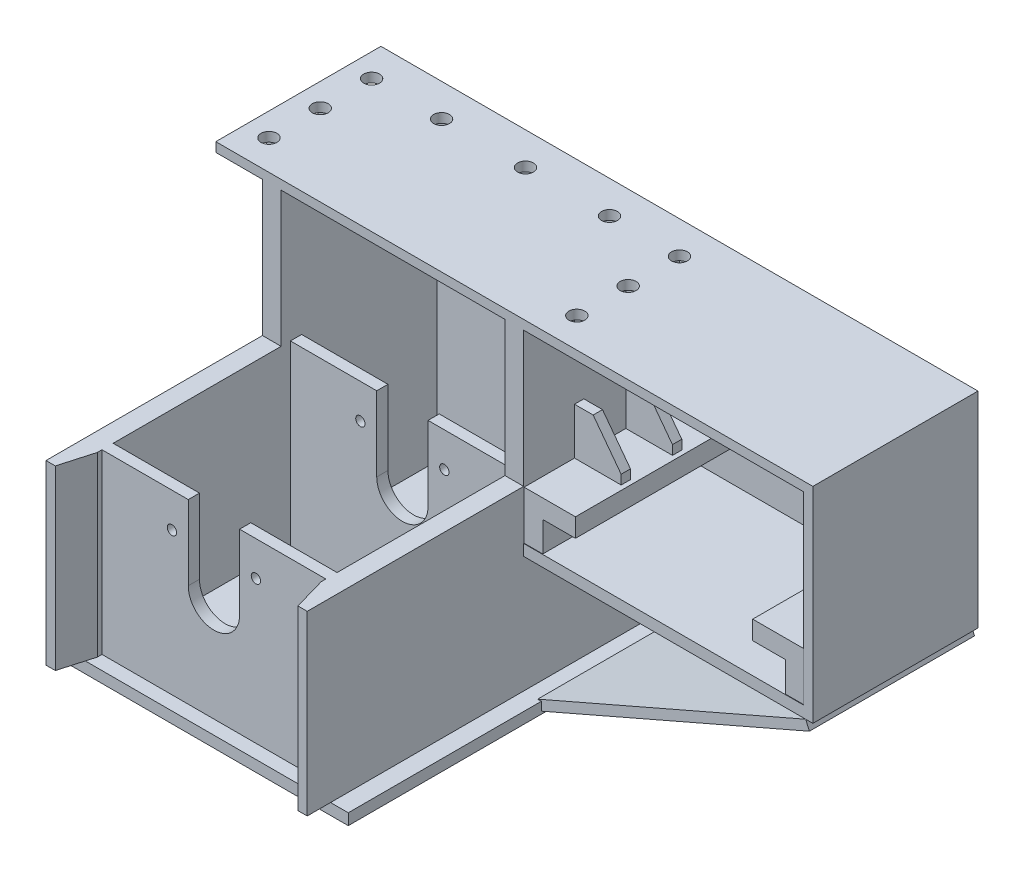
SolidWorks part; units mm, degrees
ref_plane "前视基准面" through (0, 0, 0) normal (0, 0, 1) x (1, 0, 0)
ref_plane "上视基准面" through (0, 0, 0) normal (0, 1, 0) x (1, 0, 0)
ref_plane "右视基准面" through (0, 0, 0) normal (1, 0, 0) x (0, 0, -1)
sketch "草图1" plane through (0, 0, 0) normal (0, 1, 0) x (1, 0, 0)
  line L0 (450, -858) -> (450, 49142) construction
  line L1 (0, 0) -> (640, 0)
  line L2 (0, 0) -> (0, 177)
  line L3 (0, 177) -> (640, 177)
  line L4 (640, 0) -> (640, 177)
  circle A0 centre (615, 142) radius 8.5
  circle A1 centre (615, 87) radius 8.5
  circle A2 centre (615, 32) radius 8.5
  circle A3 centre (540, 142) radius 8.5
  circle A4 centre (450, 142) radius 8.5
  circle A5 centre (360, 142) radius 8.5
  circle A6 centre (285, 142) radius 8.5
  circle A7 centre (285, 32) radius 8.5
  circle A8 centre (285, 87) radius 8.5
  dimension "D3" = 17
  dimension "D1" = 640
  dimension "D2" = 177
  dimension "D4" = 25
  dimension "D5" = 55
  dimension "D6" = 32
  dimension "D7" = 55
  dimension "D8" = 165
  dimension "D9" = 90
  dimension "D10" = 165
  dimension "D11" = 90
extrude "凸台-拉伸1" add sketch "草图1" along normal blind 10
sketch "草图2" plane through (0, 0, 0) normal (0, -1, 0) x (1, 0, 0)
  line L0 (450, -1145) -> (450, 48855) construction
  line L2 (640, -177) -> (0, -177) construction
  line L3 (590, -177) -> (570, -177)
  line L4 (590, -177) -> (590, 0)
  line L5 (590, 0) -> (570, 0)
  line L6 (570, -177) -> (570, 0)
  line L7 (0, 0) -> (640, 0) construction
  line L9 (330, -177) -> (310, -177)
  line L10 (330, -177) -> (330, 0)
  line L11 (330, 0) -> (310, 0)
  line L12 (310, -177) -> (310, 0)
  dimension "D1" = 20
  dimension "D2" = 20
  dimension "D3" = 120
  dimension "D4" = 120
extrude "凸台-拉伸2" add sketch "草图2" along normal blind 335
sketch "草图3" plane through (0, 0, 0) normal (0, 0, 1) x (1, 0, 0)
  line L0 (570, -335) -> (570, 0) construction
  line L1 (590, -335) -> (570, -335)
  line L2 (590, -335) -> (590, -145)
  line L3 (590, -145) -> (570, -145)
  line L4 (570, -335) -> (570, -145)
  line L5 (310, -335) -> (310, 0) construction
  line L6 (330, -335) -> (310, -335)
  line L7 (330, -335) -> (330, -145)
  line L8 (330, -145) -> (310, -145)
  line L9 (310, -335) -> (310, -145)
  dimension "D1" = 190
  dimension "D2" = 190
extrude "凸台-拉伸3" add sketch "草图3" along normal blind 232
sketch "草图4" plane through (0, -335, 0) normal (0, -1, 0) x (1, 0, 0)
  line L0 (330, 232) -> (320, 232)
  line L1 (310, 232) -> (330, 232) construction
  line L2 (320, 232) -> (330, 197)
  line L3 (330, -177) -> (330, 232) construction
  line L4 (330, 197) -> (330, 232)
  line L5 (570, 232) -> (580, 232)
  line L6 (570, 232) -> (590, 232) construction
  line L7 (580, 232) -> (570, 197)
  line L8 (570, 232) -> (570, -177) construction
  line L9 (570, 197) -> (570, 232)
  dimension "D1" = 35
  dimension "D2" = 10
  dimension "D3" = 10
  dimension "D4" = 35
extrude "切除-拉伸1" cut sketch "草图4" against normal through all
sketch "草图5" plane through (0, 0, 0) normal (0, -1, 0) x (-1, 0, 0)
  line L0 (-570, -197) -> (-570, 177) construction
  line L1 (-330, 177) -> (-570, 177)
  line L2 (-330, 177) -> (-330, 167)
  line L3 (-330, 167) -> (-570, 167)
  line L4 (-570, 177) -> (-570, 167)
  dimension "D1" = 10
extrude "凸台-拉伸4" add sketch "草图5" along normal blind 335
sketch "草图6" plane through (0, 0, -177) normal (0, 0, -1) x (-1, 0, 0)
  line L0 (-450, -1335) -> (-450, 48665) construction
  line L1 (-310, -335) -> (-590, -335) construction
  circle A0 centre (-450, -225) radius 35
  point P5 (-450, -335)
  dimension "D1" = 70
  dimension "D2" = 110
extrude "切除-拉伸2" cut sketch "草图6" against normal blind 10
sketch "草图7" plane through (310, 0, 0) normal (-1, 0, 0) x (0, 0, 1)
  line L0 (232, -335) -> (-177, -335) construction
  line L1 (-177, 0) -> (-167, 0)
  line L2 (-177, 0) -> (-177, -335)
  line L3 (-177, -335) -> (-167, -335)
  line L4 (-167, 0) -> (-167, -335)
  dimension "D1" = 10
extrude "凸台-拉伸5" add sketch "草图7" along normal blind 300
sketch "草图8" plane through (0, 0, -177) normal (0, 0, -1) x (-1, 0, 0)
  line L0 (-10, -211) -> (-295, -335)
  line L1 (-10, 0) -> (-10, -335) construction
  line L2 (-10, -335) -> (-590, -335) construction
  line L3 (-295, -335) -> (-10, -335)
  line L4 (-10, -335) -> (-10, -211)
  line L5 (-640, 10) -> (0, 10) construction
  circle A0 centre (-217, -76) radius 6
  circle A1 centre (-103, -76) radius 6
  circle A2 centre (-217, -119) radius 6
  circle A3 centre (-103, -119) radius 6
  dimension "D3" = 12
  dimension "D1" = 124
  dimension "D2" = 285
  dimension "D4" = 93
  dimension "D5" = 114
  dimension "D6" = 43
  dimension "D7" = 129
extrude "切除-拉伸3" cut sketch "草图8" against normal blind 10
sketch "草图9" plane through (10, 0, 0) normal (-1, 0, 0) x (0, 0, 1)
  line L1 (-177, 0) -> (0, 0)
  line L2 (-177, 0) -> (-177, -210)
  line L3 (-177, -210) -> (0, -210)
  line L4 (0, 0) -> (0, -210)
  dimension "D1" = 177
  dimension "D2" = 210
extrude "凸台-拉伸6" add sketch "草图9" along normal blind 10
sketch "草图11" plane through (0, 0, -177) normal (0, 0, -1) x (-1, 0, 0)
  line L0 (-7.7108, -210.004) -> (-295, -335)
  line L1 (-295, -335) -> (-291.0104, -344.1697)
  line L2 (-291.0104, -344.1697) -> (-3.712, -219.1697)
  line L3 (-3.712, -219.1697) -> (-7.6976, -210.0092)
  line L4 (-10, -211) -> (-295, -335) construction
  line L5 (0, -210) -> (-10, -210) construction
  line L6 (-7.6976, -210.0092) -> (-7.7108, -210.004)
  point P0 (-7.7016, -210)
  dimension "D2" = 10
extrude "凸台-拉伸7" add sketch "草图11" against normal blind 177 separate body
ref_plane "基准面1" through (0, 0, 180) normal (0, 0, 1) x (1, 0, 0)
sketch "草图12" plane through (0, 0, 180) normal (0, 0, 1) x (1, 0, 0)
  line L0 (330, -335) -> (570, -335)
  line L1 (570, -335) -> (570, -145)
  line L2 (330, -145) -> (422.5, -145)
  line L3 (330, -145) -> (330, -335)
  line L4 (450, -1335) -> (450, 48665) construction
  line L5 (-550, -225) -> (49450, -225) construction
  line L6 (422.5, -145) -> (422.5, -225)
  line L7 (570, -145) -> (477.5, -145)
  line L8 (477.5, -145) -> (477.5, -225)
  line L9 (-638.5489, -182) -> (49361.4511, -182) construction
  arc A0 (422.5, -225) -> (477.5, -225) centre (450, -225) ccw
  circle A1 centre (405, -182) radius 5
  circle A2 centre (495, -182) radius 5
  point P11 (450, -335)
  dimension "D1" = 27.5
  dimension "D3" = 10
  dimension "D2" = 43
  dimension "D4" = 45
  dimension "D5" = 45
extrude "凸台-拉伸8" add sketch "草图12" along normal blind 12
pattern_linear "阵列(线性)2" count 2 spacing 202 along (0, 0, -1) of "凸台-拉伸8"
sketch "草图14" plane through (0, 0, -167) normal (0, 0, 1) x (1, 0, 0)
  line L0 (310, -335) -> (310, 0) construction
  line L1 (10, -210) -> (310, -210)
  line L2 (10, -210) -> (10, -198)
  line L3 (10, -198) -> (310, -198)
  line L4 (310, -210) -> (310, -198)
  dimension "D1" = 12
extrude "凸台-拉伸9" add sketch "草图14" along normal blind 167
sketch "草图15" plane through (10, 0, 0) normal (1, 0, 0) x (0, 0, -1)
  line L0 (0, -198) -> (167, -198) construction
  line L1 (0.5, -166) -> (166.5, -166)
  line L2 (0.5, -166) -> (0.5, -198)
  line L3 (0.5, -198) -> (166.5, -198)
  line L4 (166.5, -166) -> (166.5, -198)
  line L5 (167, -198) -> (167, 0) construction
  line L6 (0, -198) -> (0, 0) construction
  dimension "D1" = 32
  dimension "D2" = 0.5
  dimension "D3" = 0.5
extrude "凸台-拉伸10" add sketch "草图15" along normal blind 20
sketch "草图16" plane through (0, 0, -0.5) normal (0, 0, 1) x (1, 0, 0)
  line L0 (310, -146) -> (310, -198)
  line L1 (10, -166) -> (65, -166)
  line L2 (10, -166) -> (10, -146)
  line L3 (10, -146) -> (65, -146)
  line L4 (65, -166) -> (65, -146)
  line L6 (310, -198) -> (290, -198)
  line L7 (310, -198) -> (10, -198) construction
  line L8 (290, -198) -> (290, -166)
  line L9 (290, -166) -> (255, -166)
  line L10 (255, -166) -> (255, -146)
  line L11 (255, -146) -> (310, -146)
  dimension "D1" = 55
  dimension "D2" = 20
  dimension "D3" = 20
extrude "凸台-拉伸11" add sketch "草图16" against normal blind 166
sketch "草图17" plane through (0, 0, -0.5) normal (0, 0, 1) x (1, 0, 0)
  line L0 (10, -146) -> (60, -146)
  line L2 (65, -146) -> (10, -146) construction
  line L3 (60, -146) -> (60, -136)
  line L6 (60, -136) -> (30, -96)
  line L7 (30, -96) -> (10, -96)
  line L9 (10, -96) -> (10, -146)
  line L10 (310, -146) -> (260, -146)
  line L11 (260, -146) -> (260, -136)
  line L12 (260, -136) -> (290, -96)
  line L13 (290, -96) -> (310, -96)
  line L15 (310, -96) -> (310, -146)
  dimension "D1" = 50
  dimension "D2" = 50
  dimension "D3" = 50
  dimension "D4" = 50
  dimension "D5" = 20
  dimension "D6" = 10
  dimension "D7" = 10
  dimension "D8" = 20
extrude "凸台-拉伸12" add sketch "草图17" against normal blind 166
sketch "草图18" plane through (0, -96, 0) normal (0, 1, 0) x (1, 0, 0)
  line L0 (285, 142) -> (285, 87) construction
  line L1 (285, 87) -> (285, 32) construction
  line L2 (-715, 114.5) -> (49285, 114.5) construction
  line L3 (-715, 59.5) -> (49285, 59.5) construction
  line L4 (-715, 87) -> (49285, 87) construction
  line L6 (10, 166.5) -> (310, 166.5)
  line L7 (10, 166.5) -> (10, 119.5)
  line L8 (10, 119.5) -> (310, 119.5)
  line L9 (310, 166.5) -> (310, 119.5)
  line L10 (10, 109.5) -> (310, 109.5)
  line L11 (10, 109.5) -> (10, 64.5)
  line L12 (10, 64.5) -> (310, 64.5)
  line L13 (310, 109.5) -> (310, 64.5)
  line L14 (10, 54.5) -> (310, 54.5)
  line L15 (10, 54.5) -> (10, 0.5)
  line L16 (10, 0.5) -> (310, 0.5)
  line L17 (310, 54.5) -> (310, 0.5)
  line L18 (10, 166.5) -> (10, 0.5) construction
  line L19 (310, 166.5) -> (310, 0.5) construction
  line L20 (310, 0.5) -> (290, 0.5) construction
  line L21 (310, 166.5) -> (290, 166.5) construction
  point P8 (285, 114.5)
  point P15 (285, 59.5)
  dimension "D1" = 10
  dimension "D2" = 10
extrude "切除-拉伸4" cut sketch "草图18" against normal blind 50
ref_plane "基准面2" through (590, 0, 0) normal (1, 0, 0) x (0, 0, -1)
sketch "草图20" plane through (0, 0, -54.5) normal (0, 0, 1) x (1, 0, 0)
  line L0 (590, 0) -> (640, 0)
  line L1 (640, 0) -> (640, -30)
  line L2 (640, -30) -> (610, -50)
  line L3 (610, -50) -> (590, -50)
  line L4 (590, -145) -> (590, 0) construction
  line L5 (590, -50) -> (590, 0)
  line L6 (310, 0) -> (276.6667, 0)
  line L7 (10, 0) -> (310, 0) construction
  line L8 (276.6667, 0) -> (276.6667, -30)
  line L9 (276.6667, -30) -> (290, -50)
  line L10 (290, -50) -> (310, -50)
  line L11 (310, -198) -> (310, 0) construction
  line L12 (310, -50) -> (310, 0)
  line L13 (10, 0) -> (10, -50)
  line L14 (10, -198) -> (10, 0) construction
  line L15 (10, -50) -> (30, -50)
  line L16 (30, -50) -> (60, -30)
  line L17 (60, -30) -> (60, 0)
  line L18 (60, 0) -> (10, 0)
  dimension "D1" = 20
  dimension "D2" = 30
  dimension "D3" = 30
  dimension "D4" = 30
  dimension "D5" = 50
  dimension "D6" = 50
extrude "凸台-拉伸13" add sketch "草图20" against normal blind 10
pattern_linear "阵列(线性)1" count 2 spacing 55 along (0, 0, -1) of "凸台-拉伸13"
sketch "草图21" plane through (0, -335, 0) normal (0, -1, 0) x (-1, 0, 0)
  line L1 (-291.0104, 177) -> (-605, 177)
  line L2 (-291.0104, 177) -> (-291.0104, -207)
  line L3 (-291.0104, -207) -> (-605, -207)
  line L4 (-605, 177) -> (-605, -207)
  line L6 (-291.0104, 0) -> (-291.0104, 177) construction
  line L7 (-295, 177) -> (-590, 177) construction
  line L8 (-295, 0) -> (-295, 177) construction
  dimension "D1" = 310
  dimension "D2" = 384
extrude "凸台-拉伸18" add sketch "草图21" along normal blind 12
mirror "镜向1" about plane through (0, 0, 0) normal (1, 0, 0) of bodies 129
sketch "草图22" plane through (0, 10, 0) normal (0, 1, 0) x (1, 0, 0)
  line L0 (640, 0) -> (640, 177) construction
  line L1 (0, 177) -> (640, 177)
  line L2 (0, 177) -> (0, -232)
  line L3 (0, -232) -> (640, -232)
  line L4 (640, 177) -> (640, -232)
  line L5 (640, 177) -> (-640, 177) construction
  line L6 (320, -232) -> (310, -232) construction
extrude "切除-拉伸5" cut sketch "草图22" against normal through all
